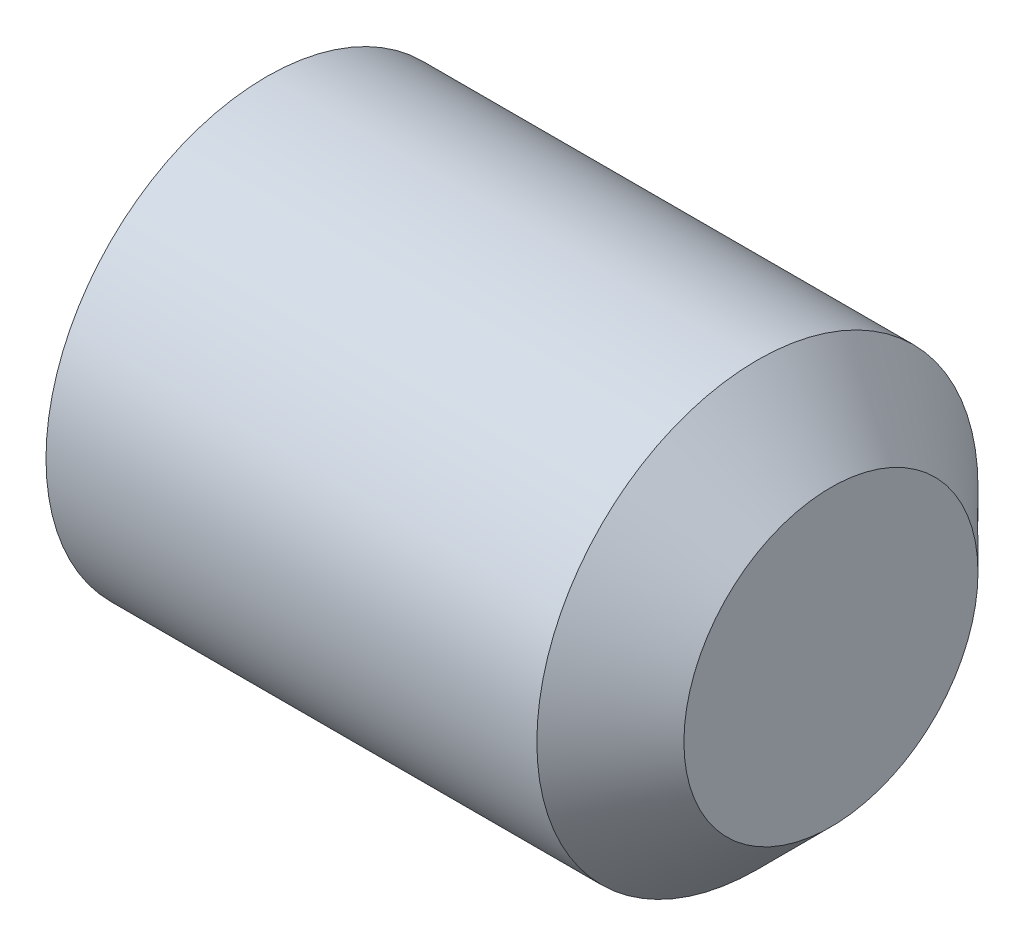
SolidWorks part; units mm, degrees
revolve "BaseBody" add sketch "BodySke" angle 360 about L5
sketch "BodySke" plane through (0, 0, 0) normal (0, 0, 1) x (1, 0, 0)
  line L0 (0, 0) -> (0, 1.2195)
  line L1 (0, 1.2195) -> (0.1619, 1.5)
  line L2 (0.1619, 1.5) -> (3.5, 1.5)
  line L3 (3.5, 1.5) -> (4, 1)
  line L4 (4, 0) -> (0, 0)
  line L5 (-12.7, 0) -> (88.9, 0) construction
  line L6 (4, 1) -> (4, 0)
  line L7 (4, 1) -> (4, 10.525) construction
  line L8 (0, -1.2195) -> (0.1619, -1.5) construction
  line L9 (0.5, 15.875) -> (0.5, -3.175) construction
  line L10 (3.5, -1.5) -> (4, -1) construction
  dimension "Diameter" = 3
  dimension "Drive_ch_ang" = 60
  dimension "Minor_dia" = 2.439
  dimension "Cup_nose_ang" = 45
  dimension "Cup_dia" = 2
  dimension "Length" = 4
  dimension "Advance" = 0.5
cosmetic thread "ThreadCosmetic" parameters "Thread_minor"=2.439
ref_plane "Plane1" through (0, 0, 0) normal (0, 0, 1) x (1, 0, 0)
ref_plane "Plane2" through (0, 0, 0) normal (0, 1, 0) x (1, 0, 0)
ref_plane "Plane3" through (0, 0, 0) normal (1, 0, 0) x (0, 0, -1)
sketch "Sketch2" plane through (0, 0, 0) normal (-1, 0, 0) x (0, 0, 1)
  line L0 (0.433, 0.75) -> (-0.433, 0.75)
  line L1 (-0.433, 0.75) -> (-0.866, 0)
  line L2 (0.433, 0.75) -> (0.866, 0)
  line L3 (0.433, -0.75) -> (0.866, 0)
  line L4 (0.433, -0.75) -> (-0.433, -0.75)
  line L5 (-0.433, -0.75) -> (-0.866, 0)
  dimension "Hex_size" = 1.5
  dimension "D2" = 0.75
  dimension "D3" = 0.75
extrude "Hex" cut sketch "Sketch2" against normal blind 2
sketch "ThdSchSke" plane through (0, 0, 0) normal (0, 0, 1) x (1, 0, 0)
  line L0 (0.1619, -1.2195) -> (-0.0345, -1.5)
  line L1 (0.1619, -1.2195) -> (0.3584, -1.5)
  line L2 (0.3584, -1.5) -> (0.3584, -1.875)
  line L3 (-3.175, 0) -> (5.1513, 0) construction
  line L5 (0.3584, -1.875) -> (-0.0345, -1.875)
  line L6 (-0.0345, -1.875) -> (-0.0345, -1.5)
  line L8 (0.1619, 1.5) -> (0.1619, -1.5) construction
  dimension "Thread_minor" = 2.439
  dimension "Diameter" = 3
revolve "ThreadSchematic" [suppressed] cut sketch "ThdSchSke" angle 360 about L3
pattern_linear "ThdSchPat" [suppressed]
equation "\"D2@Sketch2\" = \"Hex_size@Sketch2\" / 2"
equation "\"D3@Sketch2\" = \"Hex_size@Sketch2\" / 2"
equation "\"Thread_minor@ThreadCosmetic\" = \"Minor_dia@BodySke\""
equation "\"Thread_minor@ThdSchSke\" = \"Thread_minor@ThreadCosmetic\""
equation "\"Diameter@ThdSchSke\" = \"Diameter@BodySke\""
equation "\"Overcut@ThdSchSke\" = \"Diameter@BodySke\" * 1.25"
equation "\"Num_threads@ThdSchPat\" = int( (\"Length@BodySke\" - ( ( ( \"Diameter@BodySke\" - \"Minor_dia@BodySke\" ) * 0.5 ) / tan( \"Drive_ch_ang@BodySke\" * 0.017453292 ) ) - ( ( ( \"Diameter@BodySke\" - \"Cup_dia@BodySke\" ) * 0.5 ) * tan( \"Cup_nose_ang@BodySke\" * 0.017453292 ) ) ) / \"Advance@BodySke\" + 0.999 )  + 1"
equation "\"Advance@ThdSchPat\" = (\"Length@BodySke\" - ( ( ( \"Diameter@BodySke\" - \"Minor_dia@BodySke\" ) * 0.5 ) / tan( \"Drive_ch_ang@BodySke\" * 0.017453292 ) ) - ( ( ( \"Diameter@BodySke\" - \"Cup_dia@BodySke\" ) * 0.5 ) * tan( \"Cup_nose_ang@BodySke\" * 0.017453292 ) ) ) /  (\"Num_threads@ThdSchPat\" - 1) 'relax it"
equation "' \"Num_threads@ThdSchPat\" = \"Num_threads@ThdSchPat\" - sgn( \"Num_threads@ThdSchPat\" - 1) '---chamfered tips only---"
